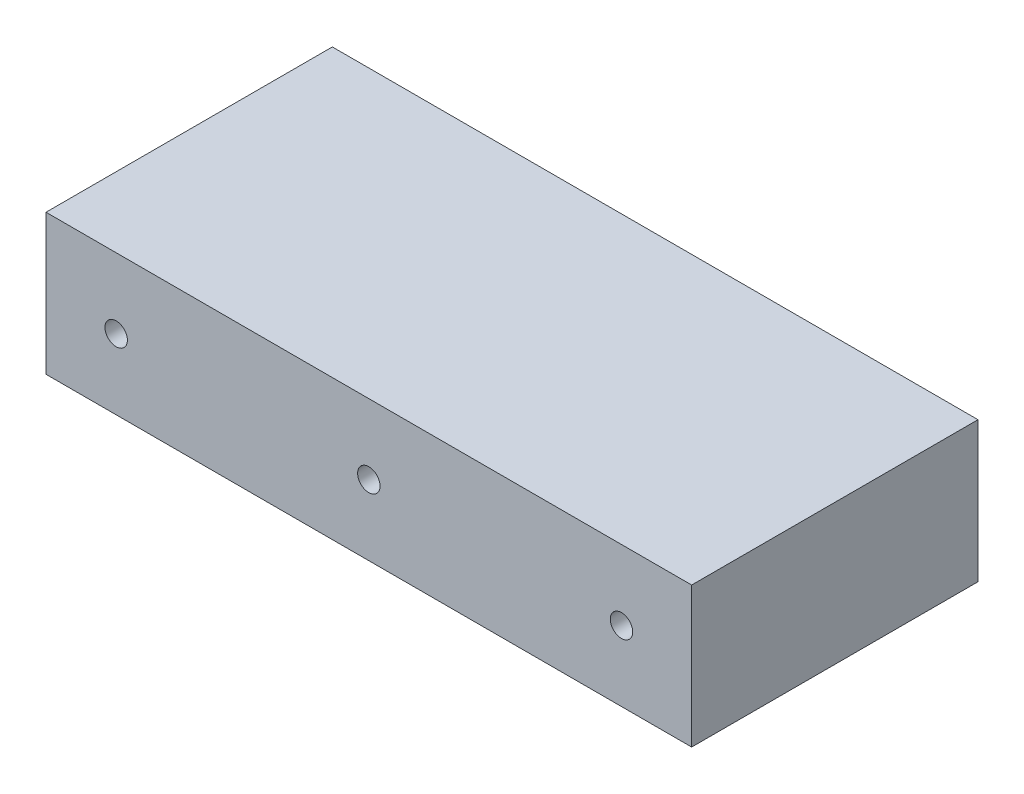
SolidWorks part; units mm, degrees
ref_plane "Front Plane" through (0, 0, 0) normal (0, 0, 1) x (1, 0, 0)
ref_plane "Top Plane" through (0, 0, 0) normal (0, 1, 0) x (1, 0, 0)
ref_plane "Right Plane" through (0, 0, 0) normal (1, 0, 0) x (0, 0, -1)
sketch "Sketch2" plane through (0, 0, 0) normal (0, 0, 1) x (1, 0, 0)
  line L1 (115, -25) -> (-115, -25)
  line L2 (115, -25) -> (115, 25)
  line L3 (115, 25) -> (-115, 25)
  line L4 (-115, -25) -> (-115, 25)
  line L5 (115, -25) -> (-115, 25) construction
  line L6 (115, 25) -> (-115, -25) construction
  point P0 (0, 0)
  dimension "D1" = 50
  dimension "D2" = 230
extrude "Boss-Extrude1" add sketch "Sketch2" along normal blind 102
sketch "Sketch3" plane through (0, 0, 102) normal (0, 0, 1) x (1, 0, 0)
  line L0 (-115, 25) -> (-115, -25) construction
  line L1 (115, 25) -> (-115, 25) construction
  circle A0 centre (0, 0) radius 4
  circle A1 centre (90, 0) radius 4
  circle A2 centre (-90, 0) radius 4
  dimension "D1" = 8
  dimension "D2" = 25
  dimension "D3" = 90
  dimension "D4" = 90
  dimension "D5" = 25
extrude "Cut-Extrude1" cut sketch "Sketch3" against normal through all
